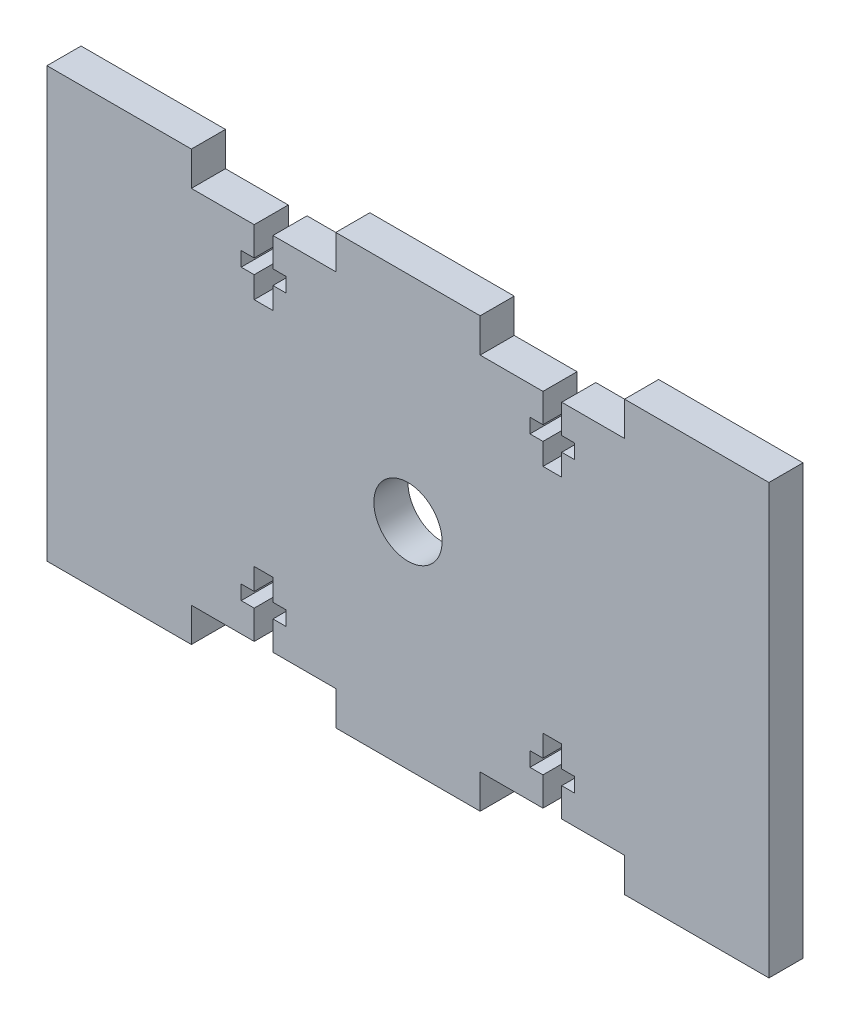
SolidWorks part; units mm, degrees
ref_plane "Front Plane" through (0, 0, 0) normal (0, 0, 1) x (1, 0, 0)
ref_plane "Top Plane" through (0, 0, 0) normal (0, 1, 0) x (1, 0, 0)
ref_plane "Right Plane" through (0, 0, 0) normal (1, 0, 0) x (0, 0, -1)
sketch "Sketch1" plane through (0, 0, 0) normal (0, 0, 1) x (1, 0, 0)
  line L0 (63.5, 75.4888) -> (63.5, 0) construction
  line L1 (25.4, 5.9944) -> (50.8, 5.9944)
  line L2 (0, 0) -> (0, 75.4888)
  line L3 (25.4, 69.4944) -> (50.8, 69.4944)
  line L4 (127, 0) -> (127, 75.4888)
  line L5 (76.2, 69.4944) -> (101.6, 69.4944)
  line L6 (127, 37.7444) -> (0, 37.7444) construction
  line L7 (0, 75.4888) -> (25.4, 75.4888)
  line L8 (25.4, 69.4944) -> (25.4, 75.4888)
  line L9 (101.6, 69.4944) -> (101.6, 75.4888)
  line L10 (50.8, 69.4944) -> (50.8, 75.4888)
  line L11 (50.8, 75.4888) -> (76.2, 75.4888)
  line L12 (76.2, 69.4944) -> (76.2, 75.4888)
  line L13 (127, 75.4888) -> (101.6, 75.4888)
  line L14 (127, 0) -> (101.6, 0)
  line L15 (76.2, 5.9944) -> (76.2, 0)
  line L16 (50.8, 0) -> (76.2, 0)
  line L17 (50.8, 5.9944) -> (50.8, 0)
  line L18 (101.6, 5.9944) -> (101.6, 0)
  line L19 (25.4, 5.9944) -> (25.4, 0)
  line L20 (0, 0) -> (25.4, 0)
  line L21 (76.2, 5.9944) -> (101.6, 5.9944)
  dimension "D1" = 25.4
  dimension "D2" = 25.4
  dimension "D3" = 127
  dimension "D4" = 5.9944
  dimension "D6" = 31.75
extrude "Boss-Extrude1" add sketch "Sketch1" along normal blind 5.9944
sketch "Sketch2" plane through (0, 0, 5.9944) normal (0, 0, 1) x (1, 0, 0)
  line L0 (63.5, 75.4888) -> (63.5, 0) construction
  line L1 (76.2, 75.4888) -> (50.8, 75.4888) construction
  line L2 (50.8, 0) -> (76.2, 0) construction
  line L3 (36.449, 69.4944) -> (36.449, 64.4144)
  line L4 (50.8, 69.4944) -> (25.4, 69.4944) construction
  line L5 (36.449, 64.4144) -> (34.163, 64.4144)
  line L6 (34.163, 64.4144) -> (34.163, 61.8744)
  line L7 (34.163, 61.8744) -> (36.449, 61.8744)
  line L8 (36.449, 61.8744) -> (36.449, 58.0644)
  line L9 (36.449, 58.0644) -> (39.751, 58.0644)
  line L10 (39.751, 58.0644) -> (39.751, 61.8744)
  line L11 (39.751, 61.8744) -> (42.037, 61.8744)
  line L12 (42.037, 61.8744) -> (42.037, 64.4144)
  line L13 (42.037, 64.4144) -> (39.751, 64.4144)
  line L14 (39.751, 64.4144) -> (39.751, 69.4944)
  line L15 (36.449, 69.4944) -> (39.751, 69.4944)
  line L16 (0, 37.7444) -> (127, 37.7444) construction
  line L17 (0, 75.4888) -> (0, 0) construction
  line L18 (127, 0) -> (127, 75.4888) construction
  line L19 (36.449, 5.9944) -> (39.751, 5.9944)
  line L20 (39.751, 11.0744) -> (39.751, 5.9944)
  line L21 (42.037, 11.0744) -> (39.751, 11.0744)
  line L22 (42.037, 13.6144) -> (42.037, 11.0744)
  line L23 (39.751, 13.6144) -> (42.037, 13.6144)
  line L24 (39.751, 17.4244) -> (39.751, 13.6144)
  line L25 (36.449, 17.4244) -> (39.751, 17.4244)
  line L26 (36.449, 13.6144) -> (36.449, 17.4244)
  line L27 (34.163, 13.6144) -> (36.449, 13.6144)
  line L28 (34.163, 11.0744) -> (34.163, 13.6144)
  line L29 (36.449, 11.0744) -> (34.163, 11.0744)
  line L30 (36.449, 5.9944) -> (36.449, 11.0744)
  line L31 (90.551, 5.9944) -> (90.551, 11.0744)
  line L32 (90.551, 11.0744) -> (92.837, 11.0744)
  line L33 (92.837, 11.0744) -> (92.837, 13.6144)
  line L34 (92.837, 13.6144) -> (90.551, 13.6144)
  line L35 (90.551, 13.6144) -> (90.551, 17.4244)
  line L36 (90.551, 17.4244) -> (87.249, 17.4244)
  line L37 (87.249, 17.4244) -> (87.249, 13.6144)
  line L38 (87.249, 13.6144) -> (84.963, 13.6144)
  line L39 (84.963, 13.6144) -> (84.963, 11.0744)
  line L40 (84.963, 11.0744) -> (87.249, 11.0744)
  line L41 (87.249, 11.0744) -> (87.249, 5.9944)
  line L42 (90.551, 5.9944) -> (87.249, 5.9944)
  line L43 (90.551, 69.4944) -> (87.249, 69.4944)
  line L44 (87.249, 64.4144) -> (87.249, 69.4944)
  line L45 (84.963, 64.4144) -> (87.249, 64.4144)
  line L46 (84.963, 61.8744) -> (84.963, 64.4144)
  line L47 (87.249, 61.8744) -> (84.963, 61.8744)
  line L48 (87.249, 58.0644) -> (87.249, 61.8744)
  line L49 (90.551, 58.0644) -> (87.249, 58.0644)
  line L50 (90.551, 61.8744) -> (90.551, 58.0644)
  line L51 (92.837, 61.8744) -> (90.551, 61.8744)
  line L52 (92.837, 64.4144) -> (92.837, 61.8744)
  line L53 (90.551, 64.4144) -> (92.837, 64.4144)
  line L54 (90.551, 69.4944) -> (90.551, 64.4144)
  point P10 (38.1, 69.4944)
  point P22 (38.1, 69.4944)
  point P40 (38.1, 5.9944)
  point P65 (88.9, 5.9944)
  point P66 (88.9, 69.4944)
  dimension "D1" = 3.302
  dimension "D2" = 11.43
  dimension "D3" = 2.286
  dimension "D4" = 2.54
  dimension "D5" = 5.08
extrude "Cut-Extrude2" cut sketch "Sketch2" against normal blind 5.9944
sketch "Sketch3" plane through (0, 0, 5.9944) normal (0, 0, 1) x (1, 0, 0)
  line L0 (63.5, 75.4888) -> (63.5, 0) construction
  line L1 (76.2, 75.4888) -> (50.8, 75.4888) construction
  line L2 (50.8, 0) -> (76.2, 0) construction
  line L3 (0, 37.7444) -> (127, 37.7444) construction
  line L4 (0, 75.4888) -> (0, 0) construction
  line L5 (127, 0) -> (127, 75.4888) construction
  circle A0 centre (63.5, 37.7444) radius 6
  dimension "D1" = 12
extrude "Cut-Extrude3" cut sketch "Sketch3" against normal blind 5.9944
